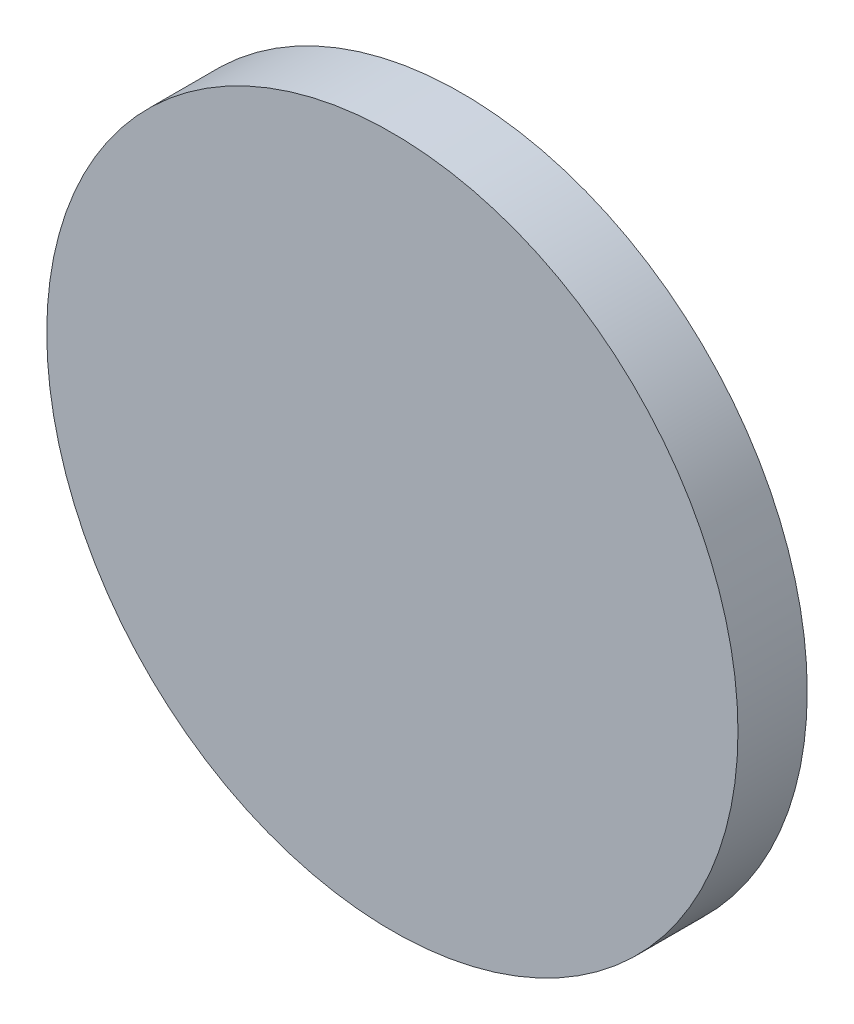
SolidWorks part; units mm, degrees
ref_plane "Plan de face" through (0, 0, 0) normal (0, 0, 1) x (1, 0, 0)
ref_plane "Plan de dessus" through (0, 0, 0) normal (0, 1, 0) x (1, 0, 0)
ref_plane "Plan de droite" through (0, 0, 0) normal (1, 0, 0) x (0, 0, -1)
sketch "Esquisse1" plane through (0, 0, 0) normal (0, 0, 1) x (1, 0, 0)
  circle A0 centre (0, 0) radius 11.625
  dimension "D1" = 23.25
extrude "Boss.-Extru.1" add sketch "Esquisse1" along normal blind 2.33
